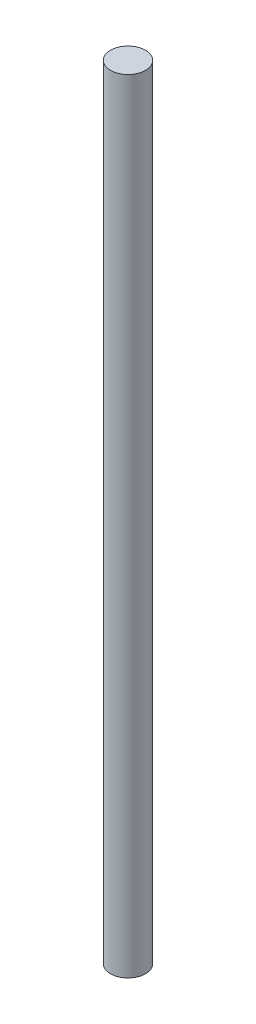
SolidWorks part; units mm, degrees
material "1023 Carbon Steel Sheet (SS)"
ref_plane "Front Plane" through (0, 0, 0) normal (0, 0, 1) x (1, 0, 0)
ref_plane "Top Plane" through (0, 0, 0) normal (0, 1, 0) x (1, 0, 0)
ref_plane "Right Plane" through (0, 0, 0) normal (1, 0, 0) x (0, 0, -1)
sketch "Sketch1" plane through (0, 0, 0) normal (0, 1, 0) x (1, 0, 0)
  circle A0 centre (0, 0) radius 3.35
  dimension "D1" = 6.7
extrude "Boss-Extrude1" add sketch "Sketch1" along normal blind 150
